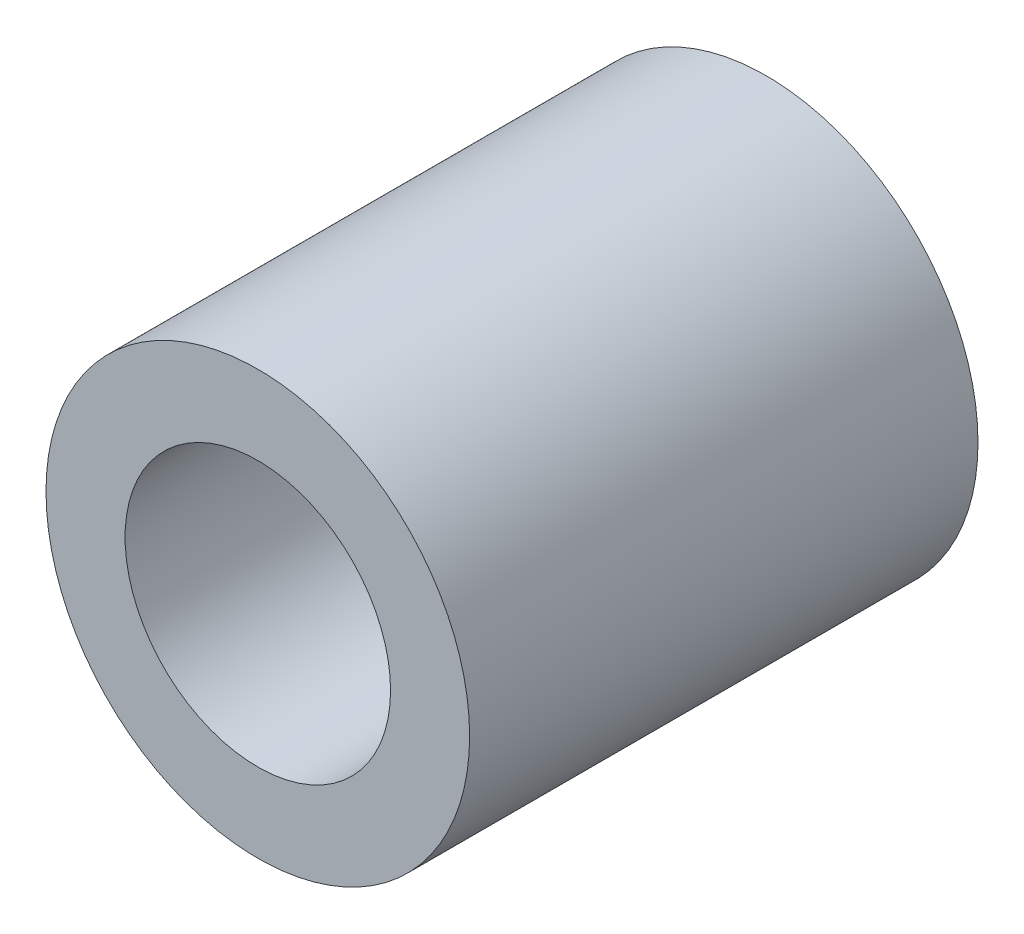
SolidWorks part; units mm, degrees
material "6061 Alloy"
ref_plane "Front Plane" through (0, 0, 0) normal (0, 0, 1) x (1, 0, 0)
ref_plane "Top Plane" through (0, 0, 0) normal (0, 1, 0) x (1, 0, 0)
ref_plane "Right Plane" through (0, 0, 0) normal (1, 0, 0) x (0, 0, -1)
sketch "Sketch1" plane through (0, 0, 0) normal (0, 0, 1) x (1, 0, 0)
  circle A0 centre (0, 0) radius 4.7625
  circle A1 centre (0, 0) radius 2.9845
  dimension "D1" = 9.525
  dimension "D2" = 5.969
extrude "Boss-Extrude1" add sketch "Sketch1" along normal blind 11.43
